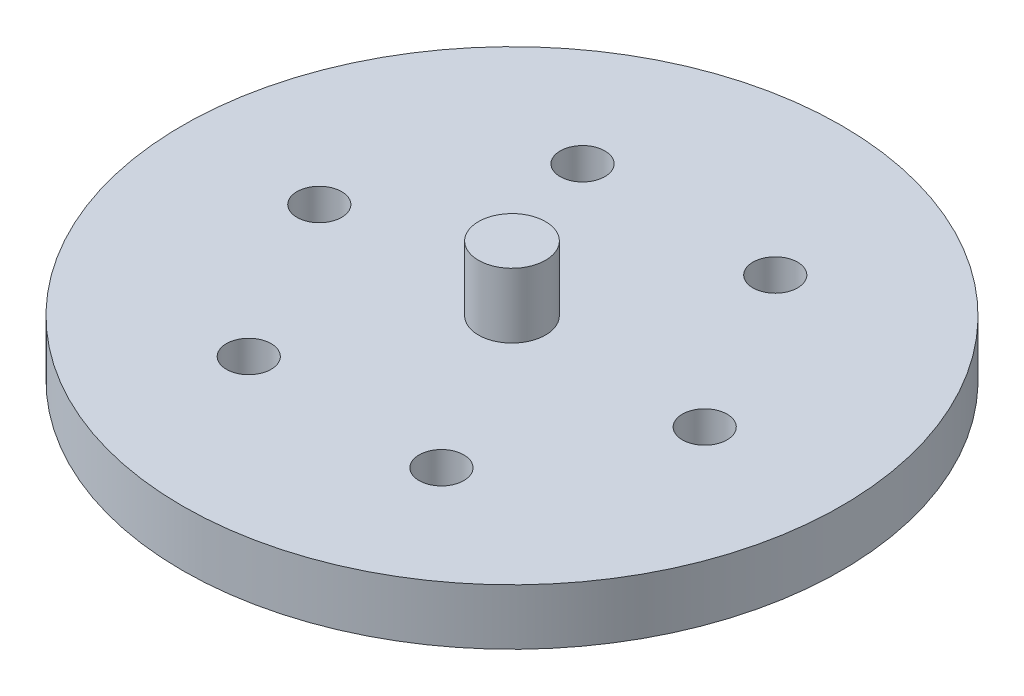
SolidWorks part; units mm, degrees
ref_plane "前视基准面" through (0, 0, 0) normal (0, 0, 1) x (1, 0, 0)
ref_plane "上视基准面" through (0, 0, 0) normal (0, 1, 0) x (1, 0, 0)
ref_plane "右视基准面" through (0, 0, 0) normal (1, 0, 0) x (0, 0, -1)
other "Configuration Table"
sketch "草图1" plane through (0, 0, 0) normal (0, 1, 0) x (1, 0, 0)
  circle A0 centre (0, 0) radius 29.5
  dimension "D1" = 59
extrude "凸台-拉伸1" add sketch "草图1" along normal blind 5
sketch "草图2" plane through (0, 5, 0) normal (0, 1, 0) x (1, 0, 0)
  circle A0 centre (0, 0) radius 3
extrude "凸台-拉伸2" add sketch "草图2" along normal blind 5.8
sketch "草图3" plane through (0, 0, 0) normal (0, -1, 0) x (1, 0, 0)
  circle A1 centre (17.25, 0) radius 2
  circle A2 centre (8.625, -14.9389) radius 2
  circle A3 centre (-8.625, -14.9389) radius 2
  circle A4 centre (-17.25, 0) radius 2
  circle A5 centre (-8.625, 14.9389) radius 2
  circle A6 centre (8.625, 14.9389) radius 2
  point P17 (0, 0)
  dimension "D2" = 6
extrude "切除-拉伸1" cut sketch "草图3" against normal blind 5
sketch "草图4" plane through (0, 0, 0) normal (0, -1, 0) x (1, 0, 0)
  circle A0 centre (0, 0) radius 3
extrude "切除-拉伸2" cut sketch "草图4" against normal blind 1
